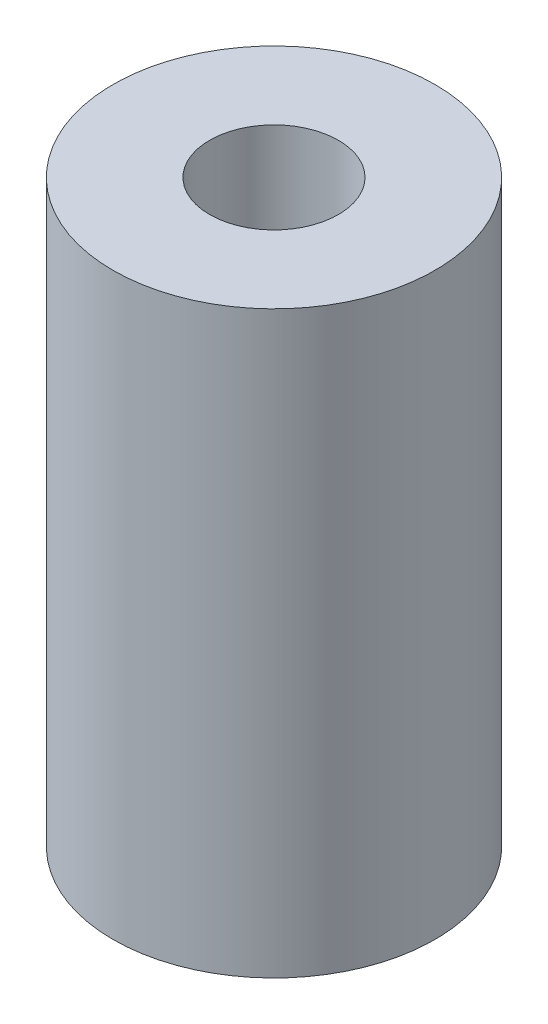
SolidWorks part; units mm, degrees
ref_plane "Front Plane" through (0, 0, 0) normal (0, 0, 1) x (1, 0, 0)
ref_plane "Top Plane" through (0, 0, 0) normal (0, 1, 0) x (1, 0, 0)
ref_plane "Right Plane" through (0, 0, 0) normal (1, 0, 0) x (0, 0, -1)
sketch "Sketch1" plane through (0, 0, 0) normal (0, 1, 0) x (1, 0, 0)
  circle A0 centre (0, 0) radius 2.5
  circle A1 centre (0, 0) radius 1
  dimension "D1" = 5
  dimension "D2" = 2
extrude "Boss-Extrude1" add sketch "Sketch1" along normal blind 9
